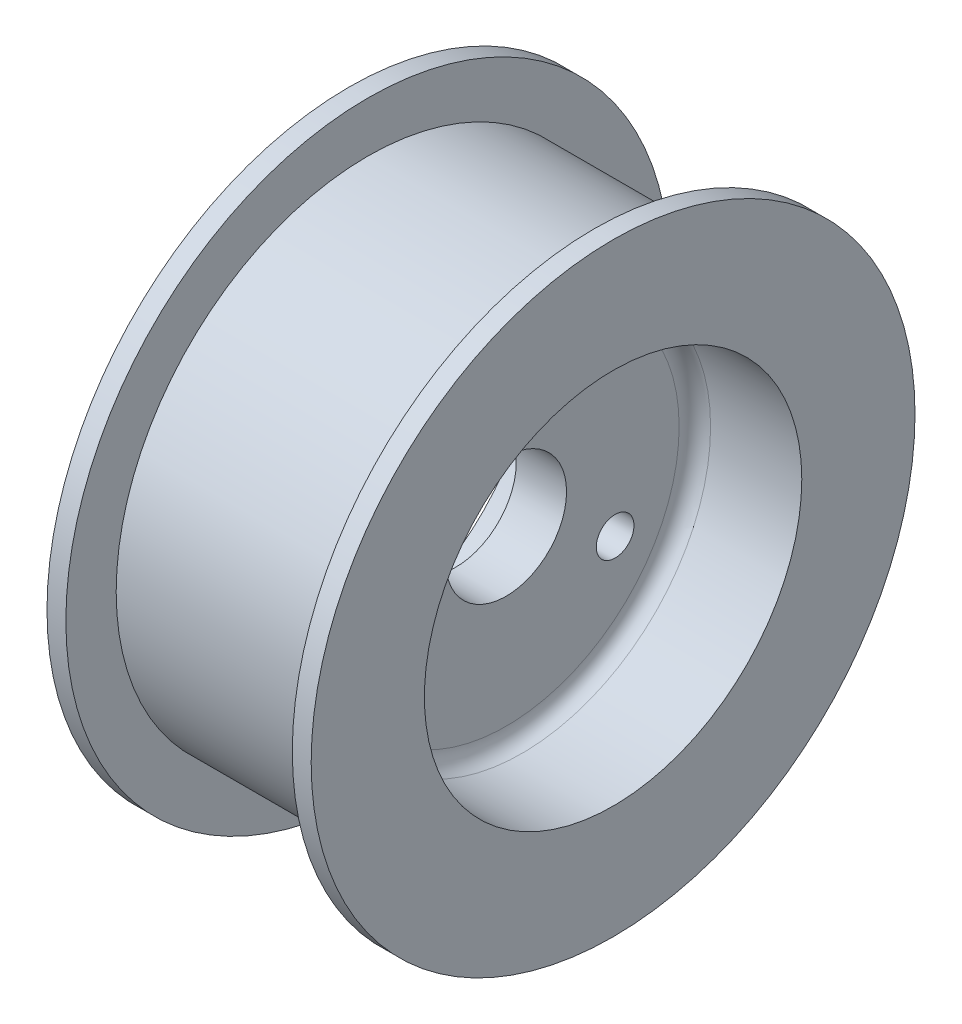
SolidWorks part; units mm, degrees
ref_plane "Front Plane" through (0, 0, 0) normal (1, 0, 0) x (0, 1, 0)
ref_plane "Top Plane" through (0, 0, 0) normal (0, 0, 1) x (0, 1, 0)
ref_plane "Right Plane" through (0, 0, 0) normal (0, 1, 0) x (-1, 0, 0)
sketch "Sketch1" plane through (0, 0, 0) normal (1, 0, 0) x (0, 1, 0)
  line L0 (-15, 0) -> (15, 0) construction
  line L1 (0, 15) -> (0, -15) construction
  circle A0 centre (0, 0) radius 15
  circle A1 centre (0, 0) radius 4.8
  circle A3 centre (10, 0) radius 1.5
  circle A4 centre (-5, -8.6603) radius 1.5
  circle A5 centre (-5, 8.6603) radius 1.5
  point P6 (-10, 0)
  dimension "D1" = 30
  dimension "D3" = 3
  dimension "D4" = 9.6
  dimension "D2" = 10
  dimension "D5" = 3
extrude "Boss-Extrude1" add sketch "Sketch1" along normal mid plane 4
sketch "Sketch2" plane through (0, 0, 0) normal (0, 1, 0) x (-1, 0, 0)
  line L0 (-2, 15) -> (-10.5, 15)
  line L1 (-10.5, 15) -> (-10.5, 20)
  line L2 (-10.5, 20) -> (10.5, 20)
  line L3 (10.5, 20) -> (10.5, 15)
  line L4 (10.5, 15) -> (2, 15)
  line L5 (2, 15) -> (-2, 15)
  point P3 (0, 20)
  dimension "D1" = 21
  dimension "D3" = 20
  dimension "D4" = 5
revolve "Revolve1" add sketch "Sketch2" angle 360 about axis through (2, 0, 0) along (-1, 0, 0)
sketch "Sketch7" plane through (0, 0, 0) normal (0, 1, 0) x (-1, 0, 0)
  line L0 (-10.5, 20) -> (-10.5, 24)
  line L1 (-10.5, 24) -> (-9, 24)
  line L2 (-9, 24) -> (-9, 20)
  line L3 (10.5, 20) -> (-10.5, 20) construction
  line L4 (-9, 20) -> (-10.5, 20)
  line L5 (10.5, 0) -> (-10.5, 0) construction
  dimension "D1" = 1.5
  dimension "D2" = 24
  dimension "D3" = 1.5
  dimension "D4" = 4
revolve "Revolve2" add sketch "Sketch7" angle 360 about axis through (2, 0, 0) along (-1, 0, 0)
mirror "Mirror1" about plane through (0, 0, 0) normal (1, 0, 0) of "Revolve2"
sketch "Sketch_Ref.Center" plane through (0, 0, 0) normal (0, 0, 1) x (0, 1, 0)
  point P0 (0, 0)
fillet "Fillet1" radius 1.25 2 edges at (-2, 0, -15) (2, 0, -15)
